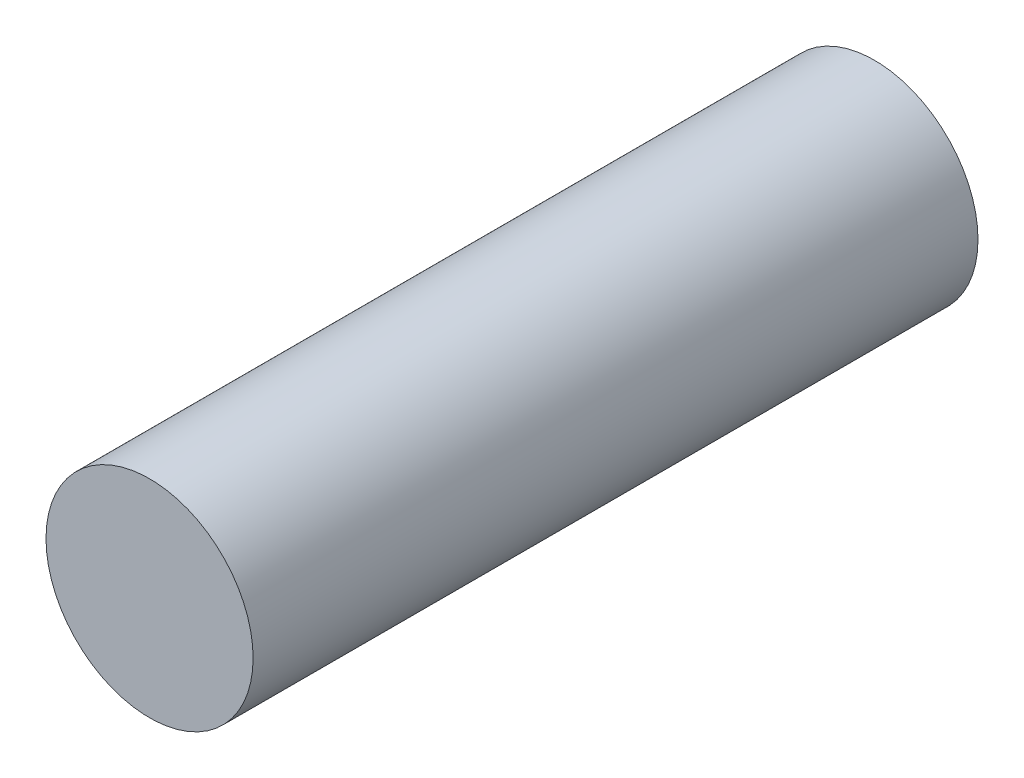
SolidWorks part; units mm, degrees
ref_plane "Front" through (0, 0, 0) normal (0, 0, 1) x (1, 0, 0)
ref_plane "Top" through (0, 0, 0) normal (0, 1, 0) x (1, 0, 0)
ref_plane "Right" through (0, 0, 0) normal (1, 0, 0) x (0, 0, -1)
other "Configuration Table"
sketch "Sketch1" plane through (0, 0, 0) normal (0, 0, 1) x (1, 0, 0)
  circle A0 centre (0, 0) radius 5 construction
  circle A1 centre (0, 0) radius 5
extrude "Extrude1" add sketch "Sketch1" against normal up to surface (35 mm away)
